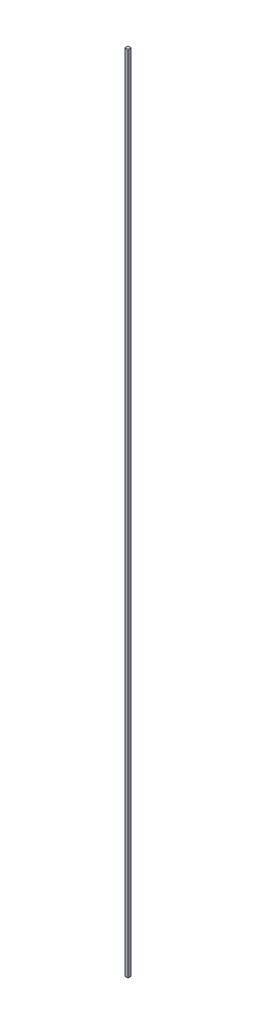
SolidWorks part; units mm, degrees
ref_plane "Front Plane" through (0, 0, 0) normal (0, 0, 1) x (1, 0, 0)
ref_plane "Top Plane" through (0, 0, 0) normal (0, 1, 0) x (1, 0, 0)
ref_plane "Right Plane" through (0, 0, 0) normal (1, 0, 0) x (0, 0, -1)
sketch "Sketch1" plane through (0, 0, 0) normal (0, 1, 0) x (1, 0, 0)
  line L1 (0, 0) -> (2, 0)
  line L2 (0, 0) -> (0, 2)
  line L3 (0, 2) -> (2, 2)
  line L4 (2, 0) -> (2, 2)
extrude "Boss-Extrude1" add sketch "Sketch1" along normal blind 509.4 flip side to cut
